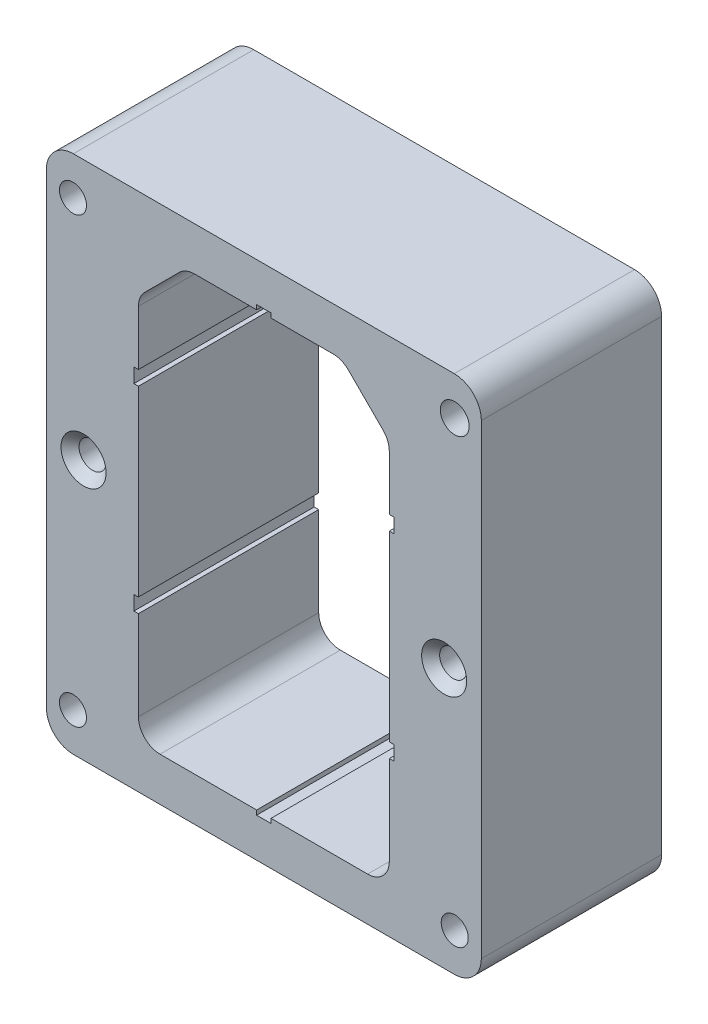
SolidWorks part; units mm, degrees
material "ABS"
ref_plane "Płaszczyzna przednia" through (0, 0, 0) normal (0, 0, 1) x (1, 0, 0)
ref_plane "Płaszczyzna górna" through (0, 0, 0) normal (0, 1, 0) x (1, 0, 0)
ref_plane "Płaszczyzna prawa" through (0, 0, 0) normal (1, 0, 0) x (0, 0, -1)
sketch "Szkic1" plane through (0, 0, 0) normal (0, 0, 1) x (1, 0, 0)
  line L0 (-14.0872, -13.3914) -> (-14.0872, -12.8914)
  line L1 (-15.6872, -13.3914) -> (-14.0872, -13.3914)
  line L2 (-15.6872, -12.8914) -> (-15.6872, -13.3914)
  line L3 (-0.9722, -0.5914) -> (-0.9722, -10.4914)
  line L4 (-3.3722, -12.8914) -> (-14.0872, -12.8914)
  line L5 (-0.9722, 21.2586) -> (-0.9722, 1.0086)
  line L6 (-0.4722, 22.8586) -> (-0.9722, 22.8586)
  line L7 (-0.9722, 21.2586) -> (-0.4722, 21.2586)
  line L8 (-0.4722, 21.2586) -> (-0.4722, 22.8586)
  line L9 (-5.5035, 34.4556) -> (-1.6751, 30.6272)
  line L10 (-0.9722, 28.9301) -> (-0.9722, 22.8586)
  line L11 (-14.0872, 35.6586) -> (-15.6872, 35.6586)
  line L12 (-15.6872, 35.6586) -> (-15.6872, 35.1586)
  line L13 (-14.0872, 35.1586) -> (-14.0872, 35.6586)
  line L14 (-14.0872, 35.1586) -> (-7.2006, 35.1586)
  line L15 (-22.5737, 35.1586) -> (-15.6872, 35.1586)
  line L16 (-28.0992, 30.6272) -> (-24.2708, 34.4556)
  line L17 (-28.8022, 22.8586) -> (-28.8022, 28.9301)
  line L18 (-28.8022, 22.8586) -> (-29.3022, 22.8586)
  line L19 (-29.3022, 21.2586) -> (-28.8022, 21.2586)
  line L20 (-29.3022, 22.8586) -> (-29.3022, 21.2586)
  line L21 (-15.6872, -12.8914) -> (-26.4022, -12.8914)
  line L22 (-28.8022, 1.0086) -> (-28.8022, 21.2586)
  line L23 (-28.8022, 1.0086) -> (-29.3022, 1.0086)
  line L24 (-29.3022, -0.5914) -> (-28.8022, -0.5914)
  line L25 (-29.3022, 1.0086) -> (-29.3022, -0.5914)
  line L26 (-28.8022, -10.4914) -> (-28.8022, -0.5914)
  line L27 (-14.8872, 35.6586) -> (-14.8872, -13.3914) construction
  line L28 (-37.8098, 35.7336) -> (-14.8872, 35.6586) construction
  line L29 (-37.8098, 35.7336) -> (-39.0098, 35.7336) construction
  line L30 (-36.0598, 37.4836) -> (-36.0598, 39.9836) construction
  line L31 (-39.0098, 35.7336) -> (-39.0098, 39.9836)
  line L32 (-39.0098, 39.9836) -> (9.2355, 39.9836)
  line L33 (-39.0098, 35.7336) -> (-39.0098, -13.4664)
  line L34 (-28.8022, 11.1336) -> (-0.9722, 11.1336) construction
  line L35 (9.2355, 35.7336) -> (9.2355, -13.4664)
  line L36 (9.2355, 35.7336) -> (9.2355, 39.9836)
  line L37 (9.2355, -13.4664) -> (9.2355, -17.7164)
  line L38 (-39.0098, -17.7164) -> (9.2355, -17.7164)
  line L39 (-39.0098, -13.4664) -> (-39.0098, -17.7164)
  line L40 (-0.4722, -0.5914) -> (-0.9722, -0.5914)
  line L41 (-0.4722, 1.0086) -> (-0.4722, -0.5914)
  line L42 (-0.9722, 1.0086) -> (-0.4722, 1.0086)
  arc A0 (-3.3722, -12.8914) -> (-0.9722, -10.4914) centre (-3.3722, -10.4914) ccw
  circle A1 centre (5.1128, 11.1336) radius 1.5
  circle A2 centre (-34.8872, 11.1336) radius 1.5
  circle A3 centre (-36.0598, -13.4664) radius 1.75 construction
  circle A4 centre (6.2855, -13.4664) radius 1.75 construction
  circle A5 centre (6.2855, 35.7336) radius 1.75 construction
  circle A6 centre (-36.0598, 35.7336) radius 1.75 construction
  arc A7 (-0.9722, 28.9301) -> (-1.6751, 30.6272) centre (-3.3722, 28.9301) ccw
  arc A8 (-22.5737, 35.1586) -> (-24.2708, 34.4556) centre (-22.5737, 32.7586) ccw
  arc A9 (-28.0992, 30.6272) -> (-28.8022, 28.9301) centre (-26.4022, 28.9301) ccw
  arc A10 (-28.8022, -10.4914) -> (-26.4022, -12.8914) centre (-26.4022, -10.4914) ccw
  arc A11 (-7.2006, 35.1586) -> (-5.5035, 34.4556) centre (-7.2006, 32.7586) cw
  circle A12 centre (6.2855, -13.4664) radius 1.5
  circle A13 centre (6.2855, 35.7336) radius 1.6
  circle A14 centre (-36.0598, 35.7336) radius 1.5
  circle A15 centre (-36.0598, -13.4664) radius 1.5
  point P66 (-14.8872, 39.9836)
  point P67 (9.2355, 11.1336)
  point P70 (-39.0098, 11.1336)
  dimension "D1" = 2.5
  dimension "D2" = 1.2
extrude "Dodanie-wyciągnięcie1" add sketch "Szkic1" along normal blind 20
fillet "Zaokrąglenie1" radius 3 4 edges at (-39.0098, -17.7164, 10) (-39.0098, 39.9836, 10) (9.2355, 39.9836, 10) (9.2355, -17.7164, 10)
chamfer "Sfazowanie1" distance 1 angle 45 2 edges at (-33.3872, 11.1336, 20) (6.6128, 11.1336, 20)
sketch "Szkic2" plane through (0, 0, 0) normal (0, 0, -1) x (-1, 0, 0)
  circle A0 centre (36.0598, 35.7336) radius 1.5 construction
  circle A1 centre (34.8872, 11.1336) radius 1.5 construction
  circle A2 centre (36.0598, -13.4664) radius 1.5 construction
  circle A3 centre (-6.2855, 35.7336) radius 1.6 construction
  circle A4 centre (-5.1128, 11.1336) radius 1.5 construction
  circle A5 centre (-6.2855, -13.4664) radius 1.5 construction
  circle A6 centre (36.0598, 35.7336) radius 1.5
  circle A7 centre (34.8872, 11.1336) radius 1.5
  circle A8 centre (36.0598, -13.4664) radius 1.5
  circle A9 centre (-6.2855, 35.7336) radius 1.6
  circle A10 centre (-5.1128, 11.1336) radius 1.5
  circle A11 centre (-6.2855, -13.4664) radius 1.5
extrude "Dodanie-wyciągnięcie2" add sketch "Szkic2" against normal blind 0.2
